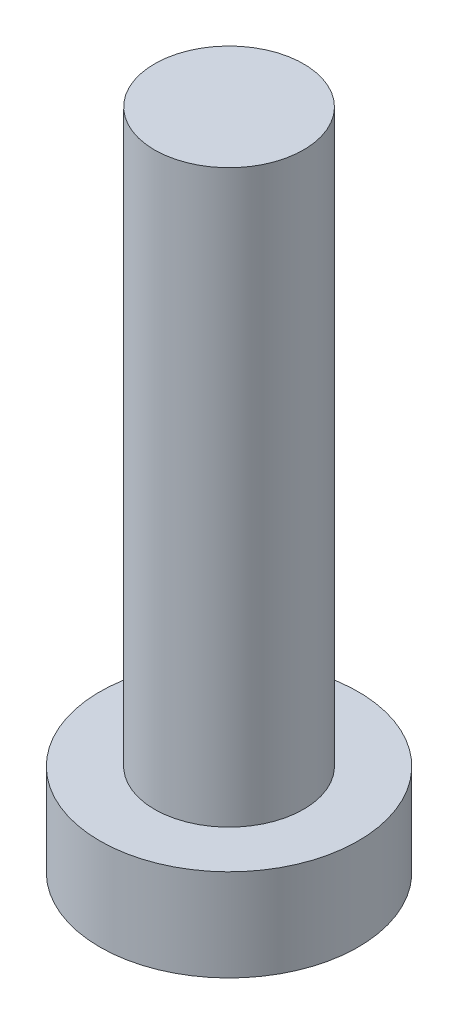
SolidWorks part; units mm, degrees
material "Plain Carbon Steel"
ref_plane "Front Plane" through (0, 0, 0) normal (0, 0, 1) x (1, 0, 0)
ref_plane "Top Plane" through (0, 0, 0) normal (0, 1, 0) x (1, 0, 0)
ref_plane "Right Plane" through (0, 0, 0) normal (1, 0, 0) x (0, 0, -1)
sketch "Sketch2" plane through (0, 0, 0) normal (0, 1, 0) x (1, 0, 0)
  circle A0 centre (0, 0) radius 2.6
  dimension "D1" = 5.2
extrude "Boss-Extrude1" add sketch "Sketch2" along normal blind 1.85
sketch "Sketch3" plane through (0, 1.85, 0) normal (0, 1, 0) x (1, 0, 0)
  circle A0 centre (0, 0) radius 1.5
  dimension "D1" = 3
extrude "Boss-Extrude2" add sketch "Sketch3" along normal blind 11.49
